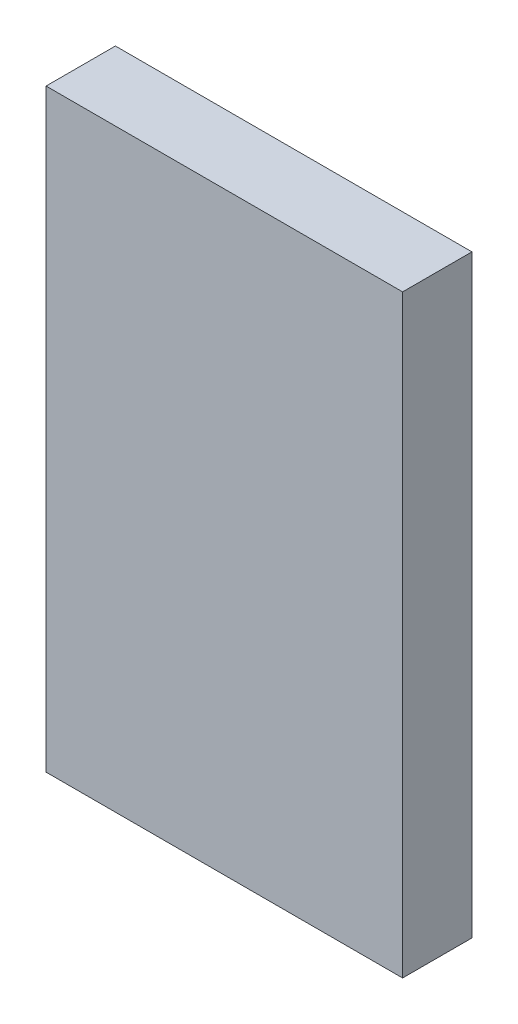
SolidWorks part; units mm, degrees
ref_plane "Plan de face" through (0, 0, 0) normal (0, 0, 1) x (1, 0, 0)
ref_plane "Plan de dessus" through (0, 0, 0) normal (0, 1, 0) x (1, 0, 0)
ref_plane "Plan de droite" through (0, 0, 0) normal (1, 0, 0) x (0, 0, -1)
sketch "Esquisse1" plane through (0, 0, 0) normal (0, 0, 1) x (1, 0, 0)
  line L1 (-18.6232, 15.0833) -> (17.3768, 15.0833)
  line L2 (-18.6232, 15.0833) -> (-18.6232, -44.9167)
  line L3 (-18.6232, -44.9167) -> (17.3768, -44.9167)
  line L4 (17.3768, 15.0833) -> (17.3768, -44.9167)
  dimension "D1" = 36
  dimension "D2" = 60
extrude "Boss.-Extru.1" add sketch "Esquisse1" along normal blind 7
